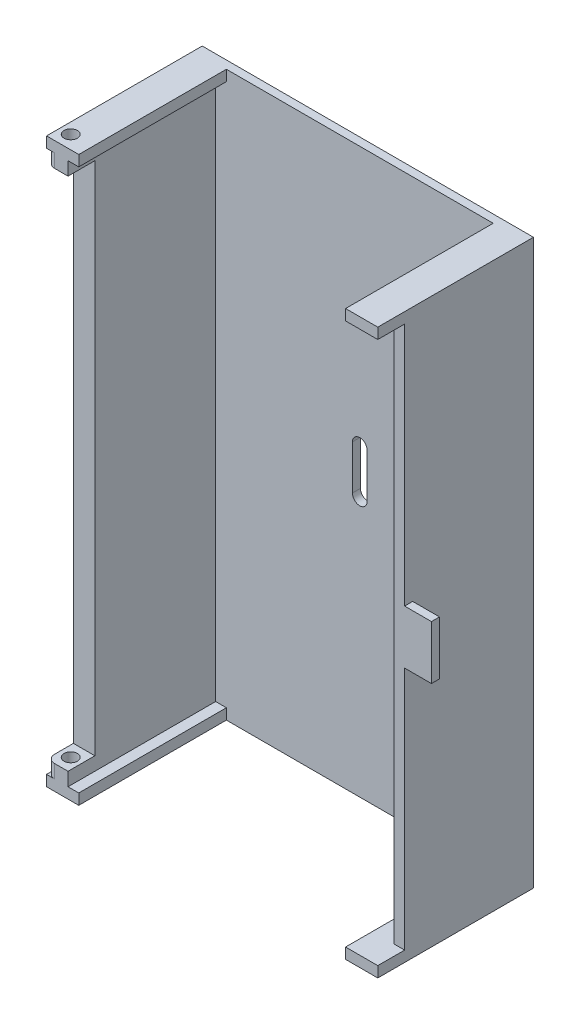
SolidWorks part; units mm, degrees
ref_plane "前基準面" through (0, 0, 0) normal (0, 0, 1) x (1, 0, 0)
ref_plane "上基準面" through (0, 0, 0) normal (0, 1, 0) x (1, 0, 0)
ref_plane "右基準面" through (0, 0, 0) normal (1, 0, 0) x (0, 0, -1)
sketch "草圖2" plane through (0, 0, 0) normal (0, 0, 1) x (1, 0, 0)
  line L1 (-58.75, 90) -> (64.65, 90)
  line L2 (-58.75, 90) -> (-58.75, -120)
  line L3 (-58.75, -120) -> (64.65, -120)
  line L4 (64.65, 90) -> (64.65, -120)
  line L5 (-58.75, 90) -> (64.65, -120) construction
  line L6 (-58.75, -120) -> (64.65, 90) construction
  point P0 (0, 0)
  dimension "D1" = 123.4
  dimension "D2" = 210
extrude "填料-伸長2" add sketch "草圖2" along normal blind 3
sketch "草圖4" plane through (0, -120, 0) normal (0, -1, 0) x (1, 0, 0)
  line L0 (-58.75, 3) -> (-58.75, 58)
  line L14 (64.65, 58) -> (64.65, 3)
  line L15 (64.65, 3) -> (-58.75, 3)
  line L16 (64.65, 3) -> (64.65, 0) construction
  arc A1 (-58.75, 58) -> (64.65, 58) centre (2.95, 58) cw
  dimension "D2" = 55
extrude "填料-伸長5" add sketch "草圖4" against normal blind 4
sketch "草圖5" plane through (0, 90, 0) normal (0, 1, 0) x (1, 0, 0)
  line L0 (-58.75, -3) -> (-58.75, -58)
  line L2 (64.65, -58) -> (64.65, -3)
  line L3 (64.65, -3) -> (-58.75, -3)
  arc A0 (-58.75, -58) -> (64.65, -58) centre (2.95, -58) ccw
extrude "填料-伸長6" add sketch "草圖5" against normal blind 4
sketch "草圖7" plane through (-58.75, 0, 0) normal (-1, 0, 0) x (0, 0, 1)
  line L0 (3, 86) -> (58, 86)
  line L1 (58, 86) -> (58, 81)
  line L2 (58, 81) -> (48, 81)
  line L4 (48, 81) -> (48, -111)
  line L6 (48, -111) -> (58, -111)
  line L7 (58, -111) -> (58, -116)
  line L8 (58, -116) -> (3, -116)
  line L9 (3, -116) -> (3, 86)
  dimension "D1" = 10
  dimension "D2" = 5
extrude "填料-伸長8" add sketch "草圖7" against normal blind 8
sketch "草圖8" plane through (0, 81, 0) normal (0, -1, 0) x (1, 0, 0)
  line L0 (-58.75, 48) -> (-58.75, 58) construction
  line L1 (-50.75, 58) -> (-58.75, 58) construction
  circle A0 centre (-54.75, 53) radius 2.5
  dimension "D1" = 5
  dimension "D2" = 4
  dimension "D3" = 5
extrude "除料-伸長1" cut sketch "草圖8" against normal through all and the other way blind 205
fillet "圓角1" radius 3 2 edges at (-58.75, -113.5, 58) (-58.75, 83.5, 58)
sketch "草圖10" plane through (0, 0, 3) normal (0, 0, 1) x (1, 0, 0)
  line L0 (60.65, 86) -> (64.65, 86)
  line L1 (64.65, 86) -> (64.65, -116)
  line L2 (64.65, -116) -> (60.65, -116)
  line L3 (60.65, -116) -> (60.65, 86)
  dimension "D1" = 4
extrude "填料-伸長9" add sketch "草圖10" along normal up to surface (45 mm away) up to face at (-54.75, -15, 48)
sketch "草圖11" plane through (0, 0, 0) normal (0, 0, -1) x (-1, 0, 0)
  line L0 (-2.75, 34.25) -> (-2.75, 17.75)
  line L1 (-9.2, 40) -> (3.3, 40)
  line L2 (-9.2, 40) -> (-9.2, -40)
  line L3 (-9.2, -40) -> (3.3, -40)
  line L4 (3.3, 40) -> (3.3, -40)
  line L5 (-9.2, 40) -> (3.3, -40) construction
  line L6 (-9.2, -40) -> (3.3, 40) construction
  line L7 (2.75, 34.25) -> (2.75, 17.75)
  line L8 (-2.95, 0) -> (10.7277, 0) construction
  line L9 (-2.95, -6.75) -> (-2.95, -23.25) construction
  line L10 (-0.2, -6.75) -> (-0.2, -23.25)
  line L11 (-5.7, -6.75) -> (-5.7, -23.25)
  line L12 (-64.65, -120) -> (-64.65, 90) construction
  line L15 (-64.65, 90) -> (58.75, 90) construction
  arc A1 (2.75, 34.25) -> (-2.75, 34.25) centre (0, 34.25) ccw
  arc A2 (-2.75, 17.75) -> (2.75, 17.75) centre (0, 17.75) ccw
  arc A3 (-0.2, -6.75) -> (-5.7, -6.75) centre (-2.95, -6.75) ccw
  arc A4 (-5.7, -23.25) -> (-0.2, -23.25) centre (-2.95, -23.25) ccw
  point P0 (0, 0)
  point P16 (-2.95, -15)
  point P21 (-2.95, -26)
  point P22 (0, 0)
  point P23 (0, 0)
  point P26 (-64.65, -15)
  point P27 (0, 0)
  point P28 (0, 0)
  point P31 (-2.95, 90)
  dimension "D1" = 80
  dimension "D3" = 5.5
  dimension "D4" = 22
  dimension "D5" = 22
  dimension "D6" = 2.75
  dimension "D2" = 12.5
extrude "除料-伸長2" cut sketch "草圖11" against normal through all
sketch "草圖12" plane through (64.65, 0, 0) normal (1, 0, 0) x (0, 0, -1)
  line L1 (-48, -5) -> (-45, -5)
  line L2 (-48, -5) -> (-48, -25)
  line L3 (-48, -25) -> (-45, -25)
  line L4 (-45, -5) -> (-45, -25)
  line L5 (-48, -5) -> (-45, -25) construction
  line L6 (-48, -25) -> (-45, -5) construction
  line L9 (-48, -116) -> (-48, 86) construction
  point P0 (-48, 0)
  point P8 (0, 0)
  point P9 (0, 0)
  point P10 (0, 0)
  dimension "D1" = 20
  dimension "D2" = 3
extrude "填料-伸長10" add sketch "草圖12" along normal blind 10
sketch "草圖13" plane through (0, 90, 0) normal (0, 1, 0) x (1, 0, 0)
  line L0 (64.65, -58) -> (64.65, 0) construction
  line L1 (52.65, -147.7273) -> (-46.75, -147.7273)
  line L2 (52.65, -147.7273) -> (52.65, -3)
  line L3 (52.65, -3) -> (-46.75, -3)
  line L4 (-46.75, -147.7273) -> (-46.75, -3)
  line L5 (-50.75, -58) -> (-55.75, -58) construction
  line L6 (-99.801, -121.3614) -> (105.701, -121.3614)
  line L7 (-58.75, -58) -> (-58.75, 0) construction
  line L8 (64.65, 0) -> (-58.75, 0) construction
  line L9 (-99.801, -121.3614) -> (-99.801, -58)
  line L14 (-99.801, -58) -> (105.701, -58)
  line L15 (105.701, -121.3614) -> (105.701, -58)
  line L16 (-99.801, -121.3614) -> (105.701, -58) construction
  line L17 (-99.801, -58) -> (105.701, -121.3614) construction
  point P0 (2.95, -75.3636)
  point P11 (2.95, -75.3636)
  point P12 (2.95, -89.6807)
  dimension "D1" = 12
  dimension "D2" = 12
  dimension "D3" = 3
extrude "除料-伸長3" cut sketch "草圖13" against normal up to surface (210 mm away) contours L6 L4 L1 L2 | L4 L14 L2 L3
